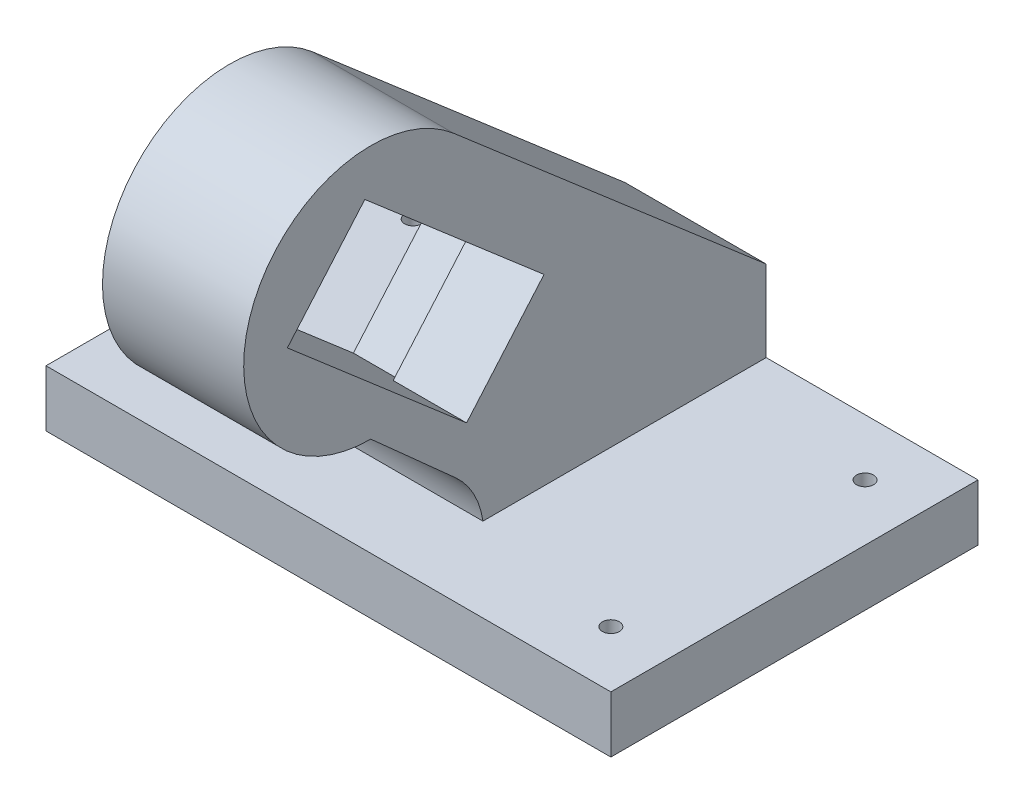
SolidWorks part; units mm, degrees
ref_plane "Front Plane" through (0, 0, 0) normal (0, 0, 1) x (1, 0, 0)
ref_plane "Top Plane" through (0, 0, 0) normal (0, 1, 0) x (1, 0, 0)
ref_plane "Right Plane" through (0, 0, 0) normal (1, 0, 0) x (0, 0, -1)
sketch "Sketch2" plane through (0, 0, 0) normal (0, 1, 0) x (1, 0, 0)
  line L1 (-50, -50) -> (50, -50)
  line L2 (-50, -50) -> (-50, 50)
  line L3 (-50, 50) -> (50, 50)
  line L4 (50, -50) -> (50, 50)
  line L5 (-50, -50) -> (50, 50) construction
  line L6 (-50, 50) -> (50, -50) construction
  point P0 (0, 0)
  dimension "D1" = 100
  dimension "D2" = 100
extrude "Boss-Extrude1" add sketch "Sketch2" along normal blind 10
sketch "Sketch3" plane through (0, 10, 0) normal (0, 1, 0) x (1, 0, 0)
  line L0 (50, 0) -> (-52.5315, 0) construction
  line L1 (50, -50) -> (50, 50) construction
  line L2 (50, 50) -> (-50, 50) construction
  line L3 (-12.5, -50) -> (12.5, -50)
  line L4 (-12.5, -50) -> (-12.5, 50)
  line L5 (-12.5, 50) -> (12.5, 50)
  line L6 (12.5, -50) -> (12.5, 50)
  line L7 (-12.5, -50) -> (12.5, 50) construction
  line L8 (-12.5, 50) -> (12.5, -50) construction
  point P5 (0, 0)
  dimension "D1" = 25
  dimension "D2" = 50
extrude "Boss-Extrude2" add sketch "Sketch3" along normal blind 100
sketch "Sketch4" plane through (-12.5, 0, 0) normal (-1, 0, 0) x (0, 0, 1)
  line L0 (50, 110) -> (50, 10) construction
  line L1 (20, 55) -> (12.0482, 48.143) construction
  line L2 (0, 10) -> (0, 7.9033)
  line L3 (-50, 10) -> (50, 10) construction
  line L4 (20, 55) -> (5.3064, 72.0396)
  line L5 (5.3064, 72.0396) -> (-66.6386, 10)
  line L6 (-15.635, 38.136) -> (26.0174, 74.0536)
  line L7 (-15.635, 38.136) -> (-1.921, 22.2323)
  line L8 (26.0174, 74.0536) -> (39.7314, 58.15)
  line L9 (-1.921, 22.2323) -> (39.7314, 58.15)
  line L10 (-10.6746, 42.4134) -> (21.0569, 69.7762)
  line L11 (-10.6746, 42.4134) -> (3.0394, 26.5098)
  line L12 (21.0569, 69.7762) -> (34.771, 53.8725)
  line L13 (3.0394, 26.5098) -> (34.771, 53.8725)
  line L14 (18.9052, 40.1912) -> (-0.1693, 62.3111) construction
  line L15 (5, 19.0836) -> (20, 32.5)
  circle A0 centre (20, 55) radius 22.5
  arc A1 (5, 19.0836) -> (0, 7.9033) centre (15, 7.9033) ccw
  line M1 (-50, 10) -> (50, 10)
  line M2 (50, 10) -> (50, 110)
  line M3 (50, 110) -> (-50, 110)
  line M4 (-50, 110) -> (-50, 10)
  dimension "D1" = 45
  dimension "D10" = 15
  dimension "D2" = 30
  dimension "D3" = 45
  dimension "D4" = 21
  dimension "D5" = 95
  dimension "D6" = 55
  dimension "D7" = 17
  dimension "D8" = 41.9
  dimension "D9" = 21
  dimension "D11" = 15
extrude "Cut-Extrude3" cut sketch "Sketch4" against normal through all both and the other way through all contours L15 A1 L5 A0 M1 M2 M3 M4
sketch "Sketch13" plane through (-12.5, 0, 0) normal (-1, 0, 0) x (0, 0, 1)
  line L0 (-15.635, 38.136) -> (-1.921, 22.2323)
  line L1 (-1.921, 22.2323) -> (3.0394, 26.5098)
  line L2 (39.7314, 58.15) -> (26.0174, 74.0536)
  line L3 (26.0174, 74.0536) -> (21.0569, 69.7762)
  line L4 (-10.6746, 42.4134) -> (21.0569, 69.7762)
  line L5 (21.0569, 69.7762) -> (34.771, 53.8725)
  line L6 (34.771, 53.8725) -> (3.0394, 26.5098)
  line L7 (3.0394, 26.5098) -> (-10.6746, 42.4134)
  line L8 (-10.6746, 42.4134) -> (-15.635, 38.136)
  line L9 (34.771, 53.8725) -> (39.7314, 58.15)
extrude "Cut-Extrude4" cut sketch "Sketch13" against normal through all both and the other way through all contours L7 L6 L5 L4
sketch "Sketch14" plane through (-12.5, 0, 0) normal (-1, 0, 0) x (0, 0, 1)
  line L0 (-15.635, 38.136) -> (-1.921, 22.2323)
  line L1 (-1.921, 22.2323) -> (39.7314, 58.15)
  line L2 (39.7314, 58.15) -> (26.0174, 74.0536)
  line L3 (26.0174, 74.0536) -> (-15.635, 38.136)
  dimension "D1" = 21
extrude "Cut-Extrude5" cut sketch "Sketch14" against normal blind 12
sketch "Sketch16" plane through (0, 0, 0) normal (0, -1, 0) x (1, 0, 0)
  line L0 (-50, 50) -> (-50, 15)
  line L1 (-50, -50) -> (-50, 50) construction
  line L2 (-50, 15) -> (50, 15)
  line L3 (50, 50) -> (50, -50) construction
  line L4 (50, 15) -> (50, 50)
  line L5 (50, 50) -> (-50, 50)
  dimension "D1" = 35
extrude "Cut-Extrude7" cut sketch "Sketch16" against normal blind 10 and the other way through all
sketch "Sketch17" plane through (0, 0, 0) normal (0, -1, 0) x (1, 0, 0)
  line L0 (50, 15) -> (-50, 15) construction
  line L1 (-50, -50) -> (-50, 15) construction
  line L2 (0, 15) -> (0, -50) construction
  line L3 (50, -50) -> (-50, -50) construction
  line L4 (0, -50) -> (-50, -17.5) construction
  line L5 (-50, -17.5) -> (50, -17.5) construction
  line L6 (50, 15) -> (50, -50) construction
  circle A0 centre (-40, 5) radius 1.5
  circle A1 centre (40, 5) radius 1.5
  circle A2 centre (40, -40) radius 1.5
  circle A3 centre (-40, -40) radius 1.5
  dimension "D1" = 3
  dimension "D2" = 10
  dimension "D3" = 10
extrude "Cut-Extrude8" cut sketch "Sketch17" against normal through all
